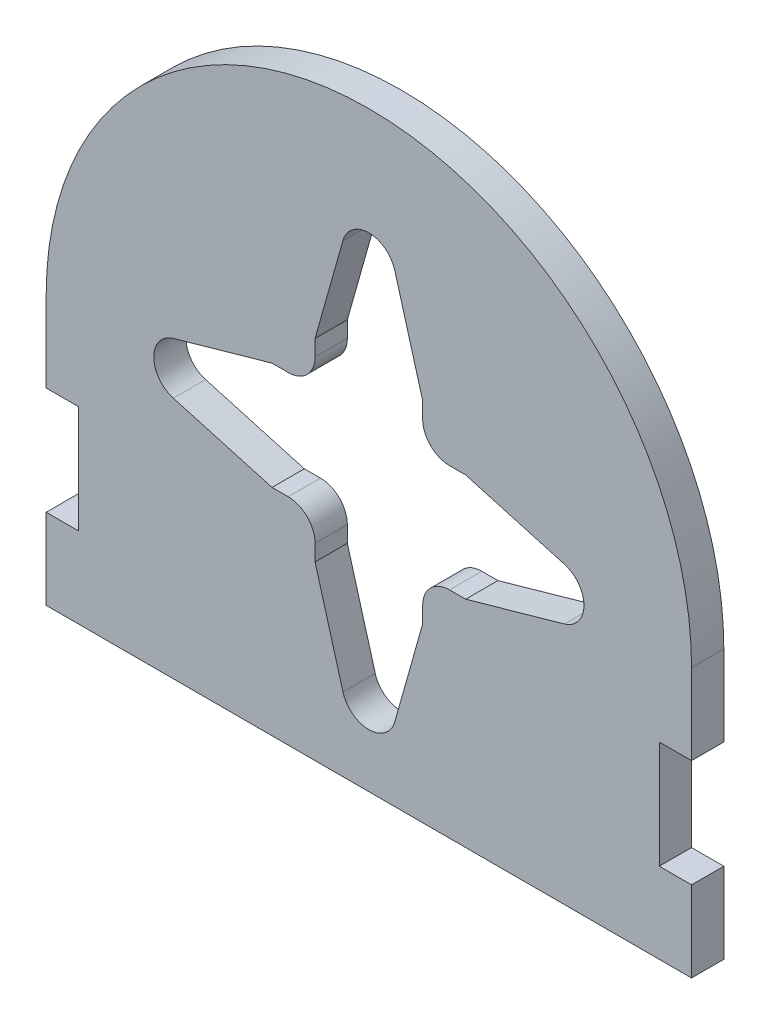
SolidWorks part; units mm, degrees
ref_plane "Front Plane" through (0, 0, 0) normal (0, 0, 1) x (1, 0, 0)
ref_plane "Top Plane" through (0, 0, 0) normal (0, 1, 0) x (1, 0, 0)
ref_plane "Right Plane" through (0, 0, 0) normal (1, 0, 0) x (0, 0, -1)
sketch "Sketch1" plane through (0, 0, 0) normal (0, 0, 1) x (1, 0, 0)
  line L0 (0, 0) -> (60, 0)
  line L1 (60, 0) -> (60, 25)
  line L2 (0, 0) -> (0, 25)
  line L3 (37.5, 20) -> (39, 20)
  line L4 (35, 16) -> (35, 17.5)
  line L5 (32.4058, 6.8201) -> (35, 16)
  line L6 (25, 16) -> (27.5942, 6.8201)
  line L7 (25, 17.5) -> (25, 16)
  line L8 (21, 20) -> (22.5, 20)
  line L9 (11.8201, 22.5942) -> (21, 20)
  line L10 (21, 30) -> (11.8201, 27.4058)
  line L11 (22.5, 30) -> (21, 30)
  line L12 (25, 34) -> (25, 32.5)
  line L13 (27.5942, 43.1799) -> (25, 34)
  line L14 (35, 34) -> (32.4058, 43.1799)
  line L15 (35, 32.5) -> (35, 34)
  line L16 (39, 30) -> (37.5, 30)
  line L17 (48.1799, 27.4058) -> (39, 30)
  line L18 (39, 20) -> (48.1799, 22.5942)
  line L19 (12.5, 25) -> (47.5, 25) construction
  line L20 (30, 42.5) -> (30, 7.5) construction
  arc A0 (60, 25) -> (0, 25) centre (30, 25) ccw
  arc A1 (37.5, 20) -> (35, 17.5) centre (37.5, 17.5) ccw
  arc A2 (27.5942, 6.8201) -> (32.4058, 6.8201) centre (30, 7.5) ccw
  arc A3 (25, 17.5) -> (22.5, 20) centre (22.5, 17.5) ccw
  arc A4 (11.8201, 27.4058) -> (11.8201, 22.5942) centre (12.5, 25) ccw
  arc A5 (22.5, 30) -> (25, 32.5) centre (22.5, 32.5) ccw
  arc A6 (32.4058, 43.1799) -> (27.5942, 43.1799) centre (30, 42.5) ccw
  arc A7 (35, 32.5) -> (37.5, 30) centre (37.5, 32.5) ccw
  arc A8 (48.1799, 22.5942) -> (48.1799, 27.4058) centre (47.5, 25) ccw
  point P3 (30, 25)
  point P39 (30, 25)
  dimension "D3" = 2.5
  dimension "D1" = 25
  dimension "D2" = 60
  dimension "D4" = 35
  dimension "D5" = 1.5
  dimension "D6" = 5
  dimension "D7" = 5
extrude "Boss-Extrude1" add sketch "Sketch1" along normal blind 3
sketch "Sketch2" plane through (0, 0, 0) normal (0, 0, -1) x (-1, 0, 0)
  line L5 (-60, 0) -> (-60, 25) construction
  line L6 (-60, 7.5) -> (-57, 7.5)
  line L7 (-60, 7.5) -> (-60, 17.5)
  line L8 (-60, 17.5) -> (-57, 17.5)
  line L9 (-57, 7.5) -> (-57, 17.5)
  line L10 (-30, 0) -> (-30, 55) construction
  line L11 (0, 0) -> (-60, 0) construction
  line L13 (-3, 7.5) -> (-3, 17.5)
  line L14 (0, 17.5) -> (-3, 17.5)
  line L15 (0, 7.5) -> (0, 17.5)
  line L16 (0, 7.5) -> (-3, 7.5)
  arc A0 (0, 25) -> (-60, 25) centre (-30, 25) ccw construction
  point P13 (-60, 12.5)
  point P14 (-60, 12.5)
  dimension "D1" = 3
  dimension "D2" = 10
extrude "Cut-Extrude1" cut sketch "Sketch2" against normal through all
ref_plane "Plane1" through (30, 0, 0) normal (-1, 0, 0) x (0, 0, 1)
